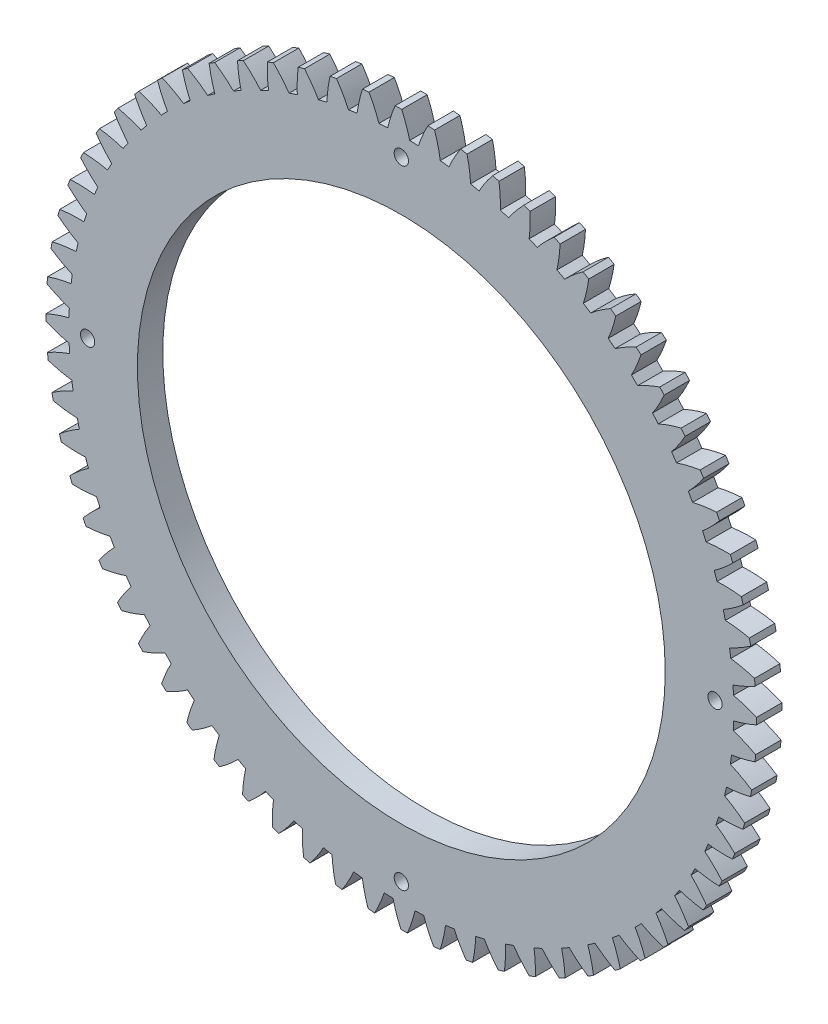
SolidWorks part; units mm, degrees
ref_plane "Front Plane" through (0, 0, 0) normal (0, 0, 1) x (1, 0, 0)
ref_plane "Top Plane" through (0, 0, 0) normal (0, 1, 0) x (1, 0, 0)
ref_plane "Right Plane" through (0, 0, 0) normal (1, 0, 0) x (0, 0, -1)
sketch "Sketch1" plane through (0, 0, 0) normal (0, 0, 1) x (1, 0, 0)
  point P0 (0, 0)
  arc B0 (-88.8869, -1.5268) -> (-83.1136, -3.414) centre (-75.3085, 30.2366) ccw
  arc B1 (-83.1136, -3.414) -> (-82.9956, -5.5911) centre (0, 0) ccw
  arc B2 (-82.9956, -5.5911) -> (-88.531, -8.0914) centre (-71.5984, -38.2007) ccw
  arc B3 (-88.531, -8.0914) -> (-88.3668, -9.7217) centre (0, 0) ccw
  arc B4 (-88.3668, -9.7217) -> (-82.4441, -11.0682) centre (-77.7771, 23.1591) ccw
  arc B5 (-82.4441, -11.0682) -> (-82.1257, -13.2251) centre (0, 0) ccw
  arc B6 (-82.1257, -13.2251) -> (-87.4068, -16.2255) centre (-67.7682, -44.644) ccw
  arc B7 (-87.4068, -16.2255) -> (-87.0929, -17.8337) centre (0, 0) ccw
  arc B8 (-87.0929, -17.8337) -> (-81.0711, -18.628) centre (-79.5822, 15.8839) ccw
  arc B9 (-81.0711, -18.628) -> (-80.5551, -20.7463) centre (0, 0) ccw
  arc B10 (-80.5551, -20.7463) -> (-85.5368, -24.2211) centre (-63.3599, -50.7065) ccw
  arc B11 (-85.5368, -24.2211) -> (-85.0759, -25.7935) centre (0, 0) ccw
  arc B12 (-85.0759, -25.7935) -> (-79.0065, -26.0288) centre (-80.7083, 8.4732) ccw
  arc B13 (-79.0065, -26.0288) -> (-78.2972, -28.0905) centre (0, 0) ccw
  arc B14 (-78.2972, -28.0905) -> (-82.9371, -32.0102) centre (-58.411, -56.3363) ccw
  arc B15 (-82.9371, -32.0102) -> (-82.333, -33.5333) centre (0, 0) ccw
  arc B16 (-82.333, -33.5333) -> (-76.2679, -33.2076) centre (-81.1458, 0.9903) ccw
  arc B17 (-76.2679, -33.2076) -> (-75.3714, -35.195) centre (0, 0) ccw
  arc B18 (-75.3714, -35.195) -> (-79.6298, -39.5261) centre (-52.9638, -61.4854) ccw
  arc B19 (-79.6298, -39.5261) -> (-78.8877, -40.987) centre (0, 0) ccw
  arc B20 (-78.8877, -40.987) -> (-72.8785, -40.103) centre (-80.891, -6.5011) ccw
  arc B21 (-72.8785, -40.103) -> (-71.8025, -41.9992) centre (0, 0) ccw
  arc B22 (-71.8025, -41.9992) -> (-75.6431, -46.7048) centre (-47.0647, -66.11) ccw
  arc B23 (-75.6431, -46.7048) -> (-74.7694, -48.091) centre (0, 0) ccw
  arc B24 (-74.7694, -48.091) -> (-68.8674, -46.6564) centre (-79.9461, -13.9371) ccw
  arc B25 (-68.8674, -46.6564) -> (-67.621, -48.4452) centre (0, 0) ccw
  arc B26 (-67.621, -48.4452) -> (-71.011, -53.485) centre (-40.7641, -70.1706) ccw
  arc B27 (-71.011, -53.485) -> (-70.0132, -54.7847) centre (0, 0) ccw
  arc B28 (-70.0132, -54.7847) -> (-64.2687, -52.8116) centre (-78.3191, -21.2541) ccw
  arc B29 (-64.2687, -52.8116) -> (-62.8626, -54.4778) centre (0, 0) ccw
  arc B30 (-62.8626, -54.4778) -> (-65.7731, -59.8089) centre (-34.1156, -73.6325) ccw
  arc B31 (-65.7731, -59.8089) -> (-64.6596, -61.011) centre (0, 0) ccw
  arc B32 (-64.6596, -61.011) -> (-59.1217, -58.5163) centre (-76.0239, -28.3898) ccw
  arc B33 (-59.1217, -58.5163) -> (-57.5678, -60.0456) centre (0, 0) ccw
  arc B34 (-57.5678, -60.0456) -> (-59.9741, -65.6226) centre (-27.1762, -76.4662) ccw
  arc B35 (-59.9741, -65.6226) -> (-58.7544, -66.7168) centre (0, 0) ccw
  arc B36 (-58.7544, -66.7168) -> (-53.4703, -63.7217) centre (-73.0802, -35.2833) ccw
  arc B37 (-53.4703, -63.7217) -> (-51.7819, -65.1012) centre (0, 0) ccw
  arc B38 (-51.7819, -65.1012) -> (-53.6634, -70.8763) centre (-20.0048, -78.6475) ccw
  arc B39 (-53.6634, -70.8763) -> (-52.3479, -71.8534) centre (0, 0) ccw
  arc B40 (-52.3479, -71.8534) -> (-47.3627, -68.3835) centre (-69.5129, -41.8758) ccw
  arc B41 (-47.3627, -68.3835) -> (-45.5543, -69.6013) centre (0, 0) ccw
  arc B42 (-45.5543, -69.6013) -> (-46.8948, -75.5254) centre (-12.6628, -80.1578) ccw
  arc B43 (-46.8948, -75.5254) -> (-45.4948, -76.3769) centre (0, 0) ccw
  arc B44 (-45.4948, -76.3769) -> (-40.851, -72.4619) centre (-65.3525, -48.111) ccw
  arc B45 (-40.851, -72.4619) -> (-38.9379, -73.5076) centre (0, 0) ccw
  arc B46 (-38.9379, -73.5076) -> (-39.7261, -79.5301) centre (-5.2128, -80.9843) ccw
  arc B47 (-39.7261, -79.5301) -> (-38.2536, -80.2488) centre (0, 0) ccw
  arc B48 (-38.2536, -80.2488) -> (-33.9908, -75.922) centre (-60.6346, -53.9358) ccw
  arc B49 (-33.9908, -75.922) -> (-31.9894, -76.7868) centre (0, 0) ccw
  arc B50 (-31.9894, -76.7868) -> (-32.2186, -82.8563) centre (2.2818, -81.1198) ccw
  arc B51 (-32.2186, -82.8563) -> (-30.686, -83.4361) centre (0, 0) ccw
  arc B52 (-30.686, -83.4361) -> (-26.8406, -78.7344) centre (-55.3994, -59.3003) ccw
  arc B53 (-26.8406, -78.7344) -> (-24.768, -79.4108) centre (0, 0) ccw
  arc B54 (-24.768, -79.4108) -> (-24.4361, -85.4756) centre (9.7568, -80.5632) ccw
  arc B55 (-24.4361, -85.4756) -> (-22.8566, -85.9115) centre (0, 0) ccw
  arc B56 (-22.8566, -85.9115) -> (-19.4614, -80.8751) centre (-49.6915, -64.159) ccw
  arc B57 (-19.4614, -80.8751) -> (-17.3352, -81.3574) centre (0, 0) ccw
  arc B58 (-17.3352, -81.3574) -> (-16.4452, -87.3657) centre (17.1486, -79.3193) ccw
  arc B59 (-16.4452, -87.3657) -> (-14.8321, -87.654) centre (0, 0) ccw
  arc B60 (-14.8321, -87.654) -> (-11.9162, -82.3258) centre (-43.5597, -68.4703) ccw
  arc B61 (-11.9162, -82.3258) -> (-9.7545, -82.6098) centre (0, 0) ccw
  arc B62 (-9.7545, -82.6098) -> (-8.3139, -88.5104) centre (24.3941, -77.3986) ccw
  arc B63 (-8.3139, -88.5104) -> (-6.6812, -88.6486) centre (0, 0) ccw
  arc B64 (-6.6812, -88.6486) -> (-4.2693, -83.0741) centre (-37.0563, -72.1974) ccw
  arc B65 (-4.2693, -83.0741) -> (-2.0907, -83.1575) centre (0, 0) ccw
  arc B66 (-2.0907, -83.1575) -> (-0.1118, -88.8999) centre (31.4315, -74.8177) ccw
  arc B67 (-0.1118, -88.8999) -> (1.5268, -88.8869) centre (0, 0) ccw
  arc B68 (1.5268, -88.8869) -> (3.414, -83.1136) centre (-30.2366, -75.3085) ccw
  arc B69 (3.414, -83.1136) -> (5.5911, -82.9956) centre (0, 0) ccw
  arc B70 (5.5911, -82.9956) -> (8.0914, -88.531) centre (38.2007, -71.5984) ccw
  arc B71 (8.0914, -88.531) -> (9.7217, -88.3668) centre (0, 0) ccw
  arc B72 (9.7217, -88.3668) -> (11.0682, -82.4441) centre (-23.1591, -77.7771) ccw
  arc B73 (11.0682, -82.4441) -> (13.2251, -82.1257) centre (0, 0) ccw
  arc B74 (13.2251, -82.1257) -> (16.2255, -87.4068) centre (44.644, -67.7682) ccw
  arc B75 (16.2255, -87.4068) -> (17.8337, -87.0929) centre (0, 0) ccw
  arc B76 (17.8337, -87.0929) -> (18.628, -81.0711) centre (-15.8839, -79.5822) ccw
  arc B77 (18.628, -81.0711) -> (20.7463, -80.5551) centre (0, 0) ccw
  arc B78 (20.7463, -80.5551) -> (24.2211, -85.5368) centre (50.7065, -63.3599) ccw
  arc B79 (24.2211, -85.5368) -> (25.7935, -85.0759) centre (0, 0) ccw
  arc B80 (25.7935, -85.0759) -> (26.0288, -79.0065) centre (-8.4732, -80.7083) ccw
  arc B81 (26.0288, -79.0065) -> (28.0905, -78.2972) centre (0, 0) ccw
  arc B82 (28.0905, -78.2972) -> (32.0102, -82.9371) centre (56.3363, -58.411) ccw
  arc B83 (32.0102, -82.9371) -> (33.5333, -82.333) centre (0, 0) ccw
  arc B84 (33.5333, -82.333) -> (33.2076, -76.2679) centre (-0.9903, -81.1458) ccw
  arc B85 (33.2076, -76.2679) -> (35.195, -75.3714) centre (0, 0) ccw
  arc B86 (35.195, -75.3714) -> (39.5261, -79.6298) centre (61.4854, -52.9638) ccw
  arc B87 (39.5261, -79.6298) -> (40.987, -78.8877) centre (0, 0) ccw
  arc B88 (40.987, -78.8877) -> (40.103, -72.8785) centre (6.5011, -80.891) ccw
  arc B89 (40.103, -72.8785) -> (41.9992, -71.8025) centre (0, 0) ccw
  arc B90 (41.9992, -71.8025) -> (46.7048, -75.6431) centre (66.11, -47.0647) ccw
  arc B91 (46.7048, -75.6431) -> (48.091, -74.7694) centre (0, 0) ccw
  arc B92 (48.091, -74.7694) -> (46.6564, -68.8674) centre (13.9371, -79.9461) ccw
  arc B93 (46.6564, -68.8674) -> (48.4452, -67.621) centre (0, 0) ccw
  arc B94 (48.4452, -67.621) -> (53.485, -71.011) centre (70.1706, -40.7641) ccw
  arc B95 (53.485, -71.011) -> (54.7847, -70.0132) centre (0, 0) ccw
  arc B96 (54.7847, -70.0132) -> (52.8116, -64.2687) centre (21.2541, -78.3191) ccw
  arc B97 (52.8116, -64.2687) -> (54.4778, -62.8626) centre (0, 0) ccw
  arc B98 (54.4778, -62.8626) -> (59.8089, -65.7731) centre (73.6325, -34.1156) ccw
  arc B99 (59.8089, -65.7731) -> (61.011, -64.6596) centre (0, 0) ccw
  arc B100 (61.011, -64.6596) -> (58.5163, -59.1217) centre (28.3898, -76.0239) ccw
  arc B101 (58.5163, -59.1217) -> (60.0456, -57.5678) centre (0, 0) ccw
  arc B102 (60.0456, -57.5678) -> (65.6226, -59.9741) centre (76.4662, -27.1762) ccw
  arc B103 (65.6226, -59.9741) -> (66.7168, -58.7544) centre (0, 0) ccw
  arc B104 (66.7168, -58.7544) -> (63.7217, -53.4703) centre (35.2833, -73.0802) ccw
  arc B105 (63.7217, -53.4703) -> (65.1012, -51.7819) centre (0, 0) ccw
  arc B106 (65.1012, -51.7819) -> (70.8763, -53.6634) centre (78.6475, -20.0048) ccw
  arc B107 (70.8763, -53.6634) -> (71.8534, -52.3479) centre (0, 0) ccw
  arc B108 (71.8534, -52.3479) -> (68.3835, -47.3627) centre (41.8758, -69.5129) ccw
  arc B109 (68.3835, -47.3627) -> (69.6013, -45.5543) centre (0, 0) ccw
  arc B110 (69.6013, -45.5543) -> (75.5254, -46.8948) centre (80.1578, -12.6628) ccw
  arc B111 (75.5254, -46.8948) -> (76.3769, -45.4948) centre (0, 0) ccw
  arc B112 (76.3769, -45.4948) -> (72.4619, -40.851) centre (48.111, -65.3525) ccw
  arc B113 (72.4619, -40.851) -> (73.5076, -38.9379) centre (0, 0) ccw
  arc B114 (73.5076, -38.9379) -> (79.5301, -39.7261) centre (80.9843, -5.2128) ccw
  arc B115 (79.5301, -39.7261) -> (80.2488, -38.2536) centre (0, 0) ccw
  arc B116 (80.2488, -38.2536) -> (75.922, -33.9908) centre (53.9358, -60.6346) ccw
  arc B117 (75.922, -33.9908) -> (76.7868, -31.9894) centre (0, 0) ccw
  arc B118 (76.7868, -31.9894) -> (82.8563, -32.2186) centre (81.1198, 2.2818) ccw
  arc B119 (82.8563, -32.2186) -> (83.4361, -30.686) centre (0, 0) ccw
  arc B120 (83.4361, -30.686) -> (78.7344, -26.8406) centre (59.3003, -55.3994) ccw
  arc B121 (78.7344, -26.8406) -> (79.4108, -24.768) centre (0, 0) ccw
  arc B122 (79.4108, -24.768) -> (85.4756, -24.4361) centre (80.5632, 9.7568) ccw
  arc B123 (85.4756, -24.4361) -> (85.9115, -22.8566) centre (0, 0) ccw
  arc B124 (85.9115, -22.8566) -> (80.8751, -19.4614) centre (64.159, -49.6915) ccw
  arc B125 (80.8751, -19.4614) -> (81.3574, -17.3352) centre (0, 0) ccw
  arc B126 (81.3574, -17.3352) -> (87.3657, -16.4452) centre (79.3193, 17.1486) ccw
  arc B127 (87.3657, -16.4452) -> (87.654, -14.8321) centre (0, 0) ccw
  arc B128 (87.654, -14.8321) -> (82.3258, -11.9162) centre (68.4703, -43.5597) ccw
  arc B129 (82.3258, -11.9162) -> (82.6098, -9.7545) centre (0, 0) ccw
  arc B130 (82.6098, -9.7545) -> (88.5104, -8.3139) centre (77.3986, 24.3941) ccw
  arc B131 (88.5104, -8.3139) -> (88.6486, -6.6812) centre (0, 0) ccw
  arc B132 (88.6486, -6.6812) -> (83.0741, -4.2693) centre (72.1974, -37.0563) ccw
  arc B133 (83.0741, -4.2693) -> (83.1575, -2.0907) centre (0, 0) ccw
  arc B134 (83.1575, -2.0907) -> (88.8999, -0.1118) centre (74.8177, 31.4315) ccw
  arc B135 (88.8999, -0.1118) -> (88.8869, 1.5268) centre (0, 0) ccw
  arc B136 (88.8869, 1.5268) -> (83.1136, 3.414) centre (75.3085, -30.2366) ccw
  arc B137 (83.1136, 3.414) -> (82.9956, 5.5911) centre (0, 0) ccw
  arc B138 (82.9956, 5.5911) -> (88.531, 8.0914) centre (71.5984, 38.2007) ccw
  arc B139 (88.531, 8.0914) -> (88.3668, 9.7217) centre (0, 0) ccw
  arc B140 (88.3668, 9.7217) -> (82.4441, 11.0682) centre (77.7771, -23.1591) ccw
  arc B141 (82.4441, 11.0682) -> (82.1257, 13.2251) centre (0, 0) ccw
  arc B142 (82.1257, 13.2251) -> (87.4068, 16.2255) centre (67.7682, 44.644) ccw
  arc B143 (87.4068, 16.2255) -> (87.0929, 17.8337) centre (0, 0) ccw
  arc B144 (87.0929, 17.8337) -> (81.0711, 18.628) centre (79.5822, -15.8839) ccw
  arc B145 (81.0711, 18.628) -> (80.5551, 20.7463) centre (0, 0) ccw
  arc B146 (80.5551, 20.7463) -> (85.5368, 24.2211) centre (63.3599, 50.7065) ccw
  arc B147 (85.5368, 24.2211) -> (85.0759, 25.7935) centre (0, 0) ccw
  arc B148 (85.0759, 25.7935) -> (79.0065, 26.0288) centre (80.7083, -8.4732) ccw
  arc B149 (79.0065, 26.0288) -> (78.2972, 28.0905) centre (0, 0) ccw
  arc B150 (78.2972, 28.0905) -> (82.9371, 32.0102) centre (58.411, 56.3363) ccw
  arc B151 (82.9371, 32.0102) -> (82.333, 33.5333) centre (0, 0) ccw
  arc B152 (82.333, 33.5333) -> (76.2679, 33.2076) centre (81.1458, -0.9903) ccw
  arc B153 (76.2679, 33.2076) -> (75.3714, 35.195) centre (0, 0) ccw
  arc B154 (75.3714, 35.195) -> (79.6298, 39.5261) centre (52.9638, 61.4854) ccw
  arc B155 (79.6298, 39.5261) -> (78.8877, 40.987) centre (0, 0) ccw
  arc B156 (78.8877, 40.987) -> (72.8785, 40.103) centre (80.891, 6.5011) ccw
  arc B157 (72.8785, 40.103) -> (71.8025, 41.9992) centre (0, 0) ccw
  arc B158 (71.8025, 41.9992) -> (75.6431, 46.7048) centre (47.0647, 66.11) ccw
  arc B159 (75.6431, 46.7048) -> (74.7694, 48.091) centre (0, 0) ccw
  arc B160 (74.7694, 48.091) -> (68.8674, 46.6564) centre (79.9461, 13.9371) ccw
  arc B161 (68.8674, 46.6564) -> (67.621, 48.4452) centre (0, 0) ccw
  arc B162 (67.621, 48.4452) -> (71.011, 53.485) centre (40.7641, 70.1706) ccw
  arc B163 (71.011, 53.485) -> (70.0132, 54.7847) centre (0, 0) ccw
  arc B164 (70.0132, 54.7847) -> (64.2687, 52.8116) centre (78.3191, 21.2541) ccw
  arc B165 (64.2687, 52.8116) -> (62.8626, 54.4778) centre (0, 0) ccw
  arc B166 (62.8626, 54.4778) -> (65.7731, 59.8089) centre (34.1156, 73.6325) ccw
  arc B167 (65.7731, 59.8089) -> (64.6596, 61.011) centre (0, 0) ccw
  arc B168 (64.6596, 61.011) -> (59.1217, 58.5163) centre (76.0239, 28.3898) ccw
  arc B169 (59.1217, 58.5163) -> (57.5678, 60.0456) centre (0, 0) ccw
  arc B170 (57.5678, 60.0456) -> (59.9741, 65.6226) centre (27.1762, 76.4662) ccw
  arc B171 (59.9741, 65.6226) -> (58.7544, 66.7168) centre (0, 0) ccw
  arc B172 (58.7544, 66.7168) -> (53.4703, 63.7217) centre (73.0802, 35.2833) ccw
  arc B173 (53.4703, 63.7217) -> (51.7819, 65.1012) centre (0, 0) ccw
  arc B174 (51.7819, 65.1012) -> (53.6634, 70.8763) centre (20.0048, 78.6475) ccw
  arc B175 (53.6634, 70.8763) -> (52.3479, 71.8534) centre (0, 0) ccw
  arc B176 (52.3479, 71.8534) -> (47.3627, 68.3835) centre (69.5129, 41.8758) ccw
  arc B177 (47.3627, 68.3835) -> (45.5543, 69.6013) centre (0, 0) ccw
  arc B178 (45.5543, 69.6013) -> (46.8948, 75.5254) centre (12.6628, 80.1578) ccw
  arc B179 (46.8948, 75.5254) -> (45.4948, 76.3769) centre (0, 0) ccw
  arc B180 (45.4948, 76.3769) -> (40.851, 72.4619) centre (65.3525, 48.111) ccw
  arc B181 (40.851, 72.4619) -> (38.9379, 73.5076) centre (0, 0) ccw
  arc B182 (38.9379, 73.5076) -> (39.7261, 79.5301) centre (5.2128, 80.9843) ccw
  arc B183 (39.7261, 79.5301) -> (38.2536, 80.2488) centre (0, 0) ccw
  arc B184 (38.2536, 80.2488) -> (33.9908, 75.922) centre (60.6346, 53.9358) ccw
  arc B185 (33.9908, 75.922) -> (31.9894, 76.7868) centre (0, 0) ccw
  arc B186 (31.9894, 76.7868) -> (32.2186, 82.8563) centre (-2.2818, 81.1198) ccw
  arc B187 (32.2186, 82.8563) -> (30.686, 83.4361) centre (0, 0) ccw
  arc B188 (30.686, 83.4361) -> (26.8406, 78.7344) centre (55.3994, 59.3003) ccw
  arc B189 (26.8406, 78.7344) -> (24.768, 79.4108) centre (0, 0) ccw
  arc B190 (24.768, 79.4108) -> (24.4361, 85.4756) centre (-9.7568, 80.5632) ccw
  arc B191 (24.4361, 85.4756) -> (22.8566, 85.9115) centre (0, 0) ccw
  arc B192 (22.8566, 85.9115) -> (19.4614, 80.8751) centre (49.6915, 64.159) ccw
  arc B193 (19.4614, 80.8751) -> (17.3352, 81.3574) centre (0, 0) ccw
  arc B194 (17.3352, 81.3574) -> (16.4452, 87.3657) centre (-17.1486, 79.3193) ccw
  arc B195 (16.4452, 87.3657) -> (14.8321, 87.654) centre (0, 0) ccw
  arc B196 (14.8321, 87.654) -> (11.9162, 82.3258) centre (43.5597, 68.4703) ccw
  arc B197 (11.9162, 82.3258) -> (9.7545, 82.6098) centre (0, 0) ccw
  arc B198 (9.7545, 82.6098) -> (8.3139, 88.5104) centre (-24.3941, 77.3986) ccw
  arc B199 (8.3139, 88.5104) -> (6.6812, 88.6486) centre (0, 0) ccw
  arc B200 (6.6812, 88.6486) -> (4.2693, 83.0741) centre (37.0563, 72.1974) ccw
  arc B201 (4.2693, 83.0741) -> (2.0907, 83.1575) centre (0, 0) ccw
  arc B202 (2.0907, 83.1575) -> (0.1118, 88.8999) centre (-31.4315, 74.8177) ccw
  arc B203 (0.1118, 88.8999) -> (-1.5268, 88.8869) centre (0, 0) ccw
  arc B204 (-1.5268, 88.8869) -> (-3.414, 83.1136) centre (30.2366, 75.3085) ccw
  arc B205 (-3.414, 83.1136) -> (-5.5911, 82.9956) centre (0, 0) ccw
  arc B206 (-5.5911, 82.9956) -> (-8.0914, 88.531) centre (-38.2007, 71.5984) ccw
  arc B207 (-8.0914, 88.531) -> (-9.7217, 88.3668) centre (0, 0) ccw
  arc B208 (-9.7217, 88.3668) -> (-11.0682, 82.4441) centre (23.1591, 77.7771) ccw
  arc B209 (-11.0682, 82.4441) -> (-13.2251, 82.1257) centre (0, 0) ccw
  arc B210 (-13.2251, 82.1257) -> (-16.2255, 87.4068) centre (-44.644, 67.7682) ccw
  arc B211 (-16.2255, 87.4068) -> (-17.8337, 87.0929) centre (0, 0) ccw
  arc B212 (-17.8337, 87.0929) -> (-18.628, 81.0711) centre (15.8839, 79.5822) ccw
  arc B213 (-18.628, 81.0711) -> (-20.7463, 80.5551) centre (0, 0) ccw
  arc B214 (-20.7463, 80.5551) -> (-24.2211, 85.5368) centre (-50.7065, 63.3599) ccw
  arc B215 (-24.2211, 85.5368) -> (-25.7935, 85.0759) centre (0, 0) ccw
  arc B216 (-25.7935, 85.0759) -> (-26.0288, 79.0065) centre (8.4732, 80.7083) ccw
  arc B217 (-26.0288, 79.0065) -> (-28.0905, 78.2972) centre (0, 0) ccw
  arc B218 (-28.0905, 78.2972) -> (-32.0102, 82.9371) centre (-56.3363, 58.411) ccw
  arc B219 (-32.0102, 82.9371) -> (-33.5333, 82.333) centre (0, 0) ccw
  arc B220 (-33.5333, 82.333) -> (-33.2076, 76.2679) centre (0.9903, 81.1458) ccw
  arc B221 (-33.2076, 76.2679) -> (-35.195, 75.3714) centre (0, 0) ccw
  arc B222 (-35.195, 75.3714) -> (-39.5261, 79.6298) centre (-61.4854, 52.9638) ccw
  arc B223 (-39.5261, 79.6298) -> (-40.987, 78.8877) centre (0, 0) ccw
  arc B224 (-40.987, 78.8877) -> (-40.103, 72.8785) centre (-6.5011, 80.891) ccw
  arc B225 (-40.103, 72.8785) -> (-41.9992, 71.8025) centre (0, 0) ccw
  arc B226 (-41.9992, 71.8025) -> (-46.7048, 75.6431) centre (-66.11, 47.0647) ccw
  arc B227 (-46.7048, 75.6431) -> (-48.091, 74.7694) centre (0, 0) ccw
  arc B228 (-48.091, 74.7694) -> (-46.6564, 68.8674) centre (-13.9371, 79.9461) ccw
  arc B229 (-46.6564, 68.8674) -> (-48.4452, 67.621) centre (0, 0) ccw
  arc B230 (-48.4452, 67.621) -> (-53.485, 71.011) centre (-70.1706, 40.7641) ccw
  arc B231 (-53.485, 71.011) -> (-54.7847, 70.0132) centre (0, 0) ccw
  arc B232 (-54.7847, 70.0132) -> (-52.8116, 64.2687) centre (-21.2541, 78.3191) ccw
  arc B233 (-52.8116, 64.2687) -> (-54.4778, 62.8626) centre (0, 0) ccw
  arc B234 (-54.4778, 62.8626) -> (-59.8089, 65.7731) centre (-73.6325, 34.1156) ccw
  arc B235 (-59.8089, 65.7731) -> (-61.011, 64.6596) centre (0, 0) ccw
  arc B236 (-61.011, 64.6596) -> (-58.5163, 59.1217) centre (-28.3898, 76.0239) ccw
  arc B237 (-58.5163, 59.1217) -> (-60.0456, 57.5678) centre (0, 0) ccw
  arc B238 (-60.0456, 57.5678) -> (-65.6226, 59.9741) centre (-76.4662, 27.1762) ccw
  arc B239 (-65.6226, 59.9741) -> (-66.7168, 58.7544) centre (0, 0) ccw
  arc B240 (-66.7168, 58.7544) -> (-63.7217, 53.4703) centre (-35.2833, 73.0802) ccw
  arc B241 (-63.7217, 53.4703) -> (-65.1012, 51.7819) centre (0, 0) ccw
  arc B242 (-65.1012, 51.7819) -> (-70.8763, 53.6634) centre (-78.6475, 20.0048) ccw
  arc B243 (-70.8763, 53.6634) -> (-71.8534, 52.3479) centre (0, 0) ccw
  arc B244 (-71.8534, 52.3479) -> (-68.3835, 47.3627) centre (-41.8758, 69.5129) ccw
  arc B245 (-68.3835, 47.3627) -> (-69.6013, 45.5543) centre (0, 0) ccw
  arc B246 (-69.6013, 45.5543) -> (-75.5254, 46.8948) centre (-80.1578, 12.6628) ccw
  arc B247 (-75.5254, 46.8948) -> (-76.3769, 45.4948) centre (0, 0) ccw
  arc B248 (-76.3769, 45.4948) -> (-72.4619, 40.851) centre (-48.111, 65.3525) ccw
  arc B249 (-72.4619, 40.851) -> (-73.5076, 38.9379) centre (0, 0) ccw
  arc B250 (-73.5076, 38.9379) -> (-79.5301, 39.7261) centre (-80.9843, 5.2128) ccw
  arc B251 (-79.5301, 39.7261) -> (-80.2488, 38.2536) centre (0, 0) ccw
  arc B252 (-80.2488, 38.2536) -> (-75.922, 33.9908) centre (-53.9358, 60.6346) ccw
  arc B253 (-75.922, 33.9908) -> (-76.7868, 31.9894) centre (0, 0) ccw
  arc B254 (-76.7868, 31.9894) -> (-82.8563, 32.2186) centre (-81.1198, -2.2818) ccw
  arc B255 (-82.8563, 32.2186) -> (-83.4361, 30.686) centre (0, 0) ccw
  arc B256 (-83.4361, 30.686) -> (-78.7344, 26.8406) centre (-59.3003, 55.3994) ccw
  arc B257 (-78.7344, 26.8406) -> (-79.4108, 24.768) centre (0, 0) ccw
  arc B258 (-79.4108, 24.768) -> (-85.4756, 24.4361) centre (-80.5632, -9.7568) ccw
  arc B259 (-85.4756, 24.4361) -> (-85.9115, 22.8566) centre (0, 0) ccw
  arc B260 (-85.9115, 22.8566) -> (-80.8751, 19.4614) centre (-64.159, 49.6915) ccw
  arc B261 (-80.8751, 19.4614) -> (-81.3574, 17.3352) centre (0, 0) ccw
  arc B262 (-81.3574, 17.3352) -> (-87.3657, 16.4452) centre (-79.3193, -17.1486) ccw
  arc B263 (-87.3657, 16.4452) -> (-87.654, 14.8321) centre (0, 0) ccw
  arc B264 (-87.654, 14.8321) -> (-82.3258, 11.9162) centre (-68.4703, 43.5597) ccw
  arc B265 (-82.3258, 11.9162) -> (-82.6098, 9.7545) centre (0, 0) ccw
  arc B266 (-82.6098, 9.7545) -> (-88.5104, 8.3139) centre (-77.3986, -24.3941) ccw
  arc B267 (-88.5104, 8.3139) -> (-88.6486, 6.6812) centre (0, 0) ccw
  arc B268 (-88.6486, 6.6812) -> (-83.0741, 4.2693) centre (-72.1974, 37.0563) ccw
  arc B269 (-83.0741, 4.2693) -> (-83.1575, 2.0907) centre (0, 0) ccw
  arc B270 (-83.1575, 2.0907) -> (-88.8999, 0.1118) centre (-74.8177, -31.4315) ccw
  arc B271 (-88.8999, 0.1118) -> (-88.8869, -1.5268) centre (0, 0) ccw
sketch_block_instance "Block1-1"
sketch_block "Block1"
extrude "Boss-Extrude1" add sketch "Sketch1" along normal blind 6.35
sketch "Sketch3" plane through (0, 0, 6.35) normal (0, 0, 1) x (1, 0, 0)
  circle A0 centre (0, 0) radius 66.04
  point P3 (0, 0)
  dimension "D1" = 132.08
extrude "Cut-Extrude1" cut sketch "Sketch3" against normal blind 6.35
sketch "Sketch4" plane through (0, 0, 0) normal (0, 0, -1) x (-1, 0, 0)
  circle A0 centre (0, 78.5) radius 1.7859
  dimension "D1" = 3.5719
  dimension "D2" = 78.5
extrude "Cut-Extrude2" cut sketch "Sketch4" against normal blind 6.35
pattern_circular "CirPattern1" count 4 over 360 about axis through (0, 0, 0) along (0, 0, 1) of "Cut-Extrude2"
